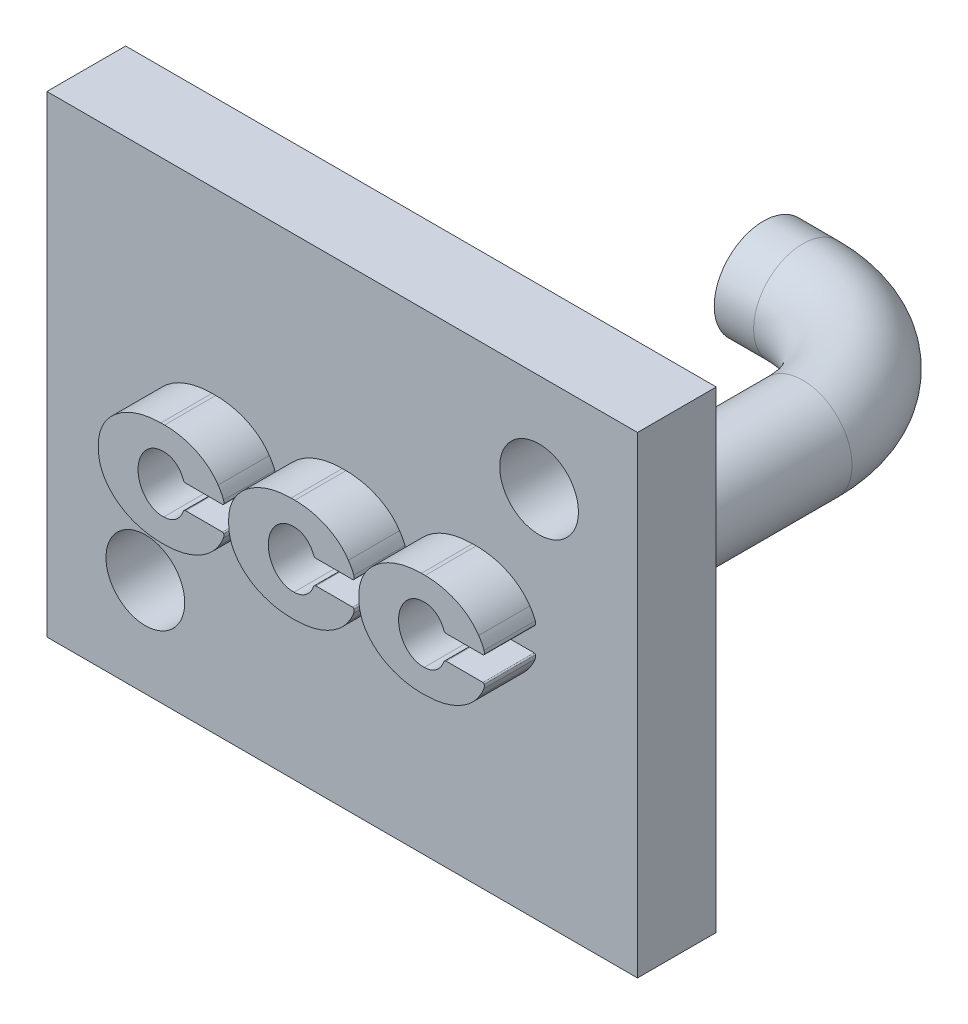
SolidWorks part; units mm, degrees
ref_plane "Front Plane" through (0, 0, 0) normal (0, 0, 1) x (1, 0, 0)
ref_plane "Top Plane" through (0, 0, 0) normal (0, 1, 0) x (1, 0, 0)
ref_plane "Right Plane" through (0, 0, 0) normal (1, 0, 0) x (0, 0, -1)
sketch "Sketch1" plane through (0, 0, 0) normal (0, 0, 1) x (1, 0, 0)
  line L1 (-7.5, 6) -> (7.5, 6)
  line L2 (-7.5, 6) -> (-7.5, -6)
  line L3 (-7.5, -6) -> (7.5, -6)
  line L4 (7.5, 6) -> (7.5, -6)
  line L5 (-7.5, 6) -> (7.5, -6) construction
  line L6 (-7.5, -6) -> (7.5, 6) construction
  point P0 (0, 0)
  dimension "D1" = 15
  dimension "D2" = 12
extrude "Boss-Extrude1" add sketch "Sketch1" along normal blind 2
sketch "Sketch2" plane through (0, 0, 2) normal (0, 0, 1) x (1, 0, 0)
  line L0 (0.6342, 0.4466) -> (1.5701, 0.4466)
  line L1 (0.0969, 1.4574) -> (0.0032, 1.4574)
  line L2 (-1.5824, 0.2062) -> (-1.5824, 0.0761)
  line L3 (0.0032, -1.1751) -> (0.0969, -1.1751)
  line L4 (1.5655, -0.1604) -> (0.6342, -0.1604)
  line L5 (-2.6741, 0.4466) -> (-1.7382, 0.4466)
  line L6 (-3.2115, 1.4574) -> (-3.3051, 1.4574)
  line L7 (-4.8907, 0.2062) -> (-4.8907, 0.0761)
  line L8 (-3.3051, -1.1751) -> (-3.2115, -1.1751)
  line L9 (-1.7428, -0.1604) -> (-2.6741, -0.1604)
  line L10 (3.9425, 0.4466) -> (4.8784, 0.4466)
  line L11 (3.4052, 1.4574) -> (3.3115, 1.4574)
  line L12 (1.7259, 0.2062) -> (1.7259, 0.0761)
  line L13 (3.3115, -1.1751) -> (3.4052, -1.1751)
  line L14 (4.8738, -0.1604) -> (3.9425, -0.1604)
  arc A0 (0.5725, 0.4902) -> (0.6342, 0.4466) centre (0.6342, 0.5121) ccw
  arc A1 (1.5701, 0.4466) -> (1.5993, 0.4715) centre (1.5656, 0.4815) ccw
  arc A2 (1.5993, 0.4715) -> (1.5951, 0.559) centre (1.4187, 0.5067) ccw
  arc A3 (1.5951, 0.559) -> (1.458, 0.8163) centre (0.5131, 0.1474) ccw
  arc A4 (1.458, -0.5339) -> (1.5904, -0.2876) centre (0.5225, 0.1277) ccw
  arc A5 (1.5904, -0.2876) -> (1.6002, -0.1896) centre (1.4189, -0.2209) ccw
  arc A6 (1.6002, -0.1896) -> (1.5655, -0.1604) centre (1.5655, -0.1956) ccw
  arc A7 (0.6342, -0.1604) -> (0.5725, -0.204) centre (0.6342, -0.2259) ccw
  arc A8 (-2.7358, 0.4902) -> (-2.6741, 0.4466) centre (-2.6741, 0.5121) ccw
  arc A9 (-1.7382, 0.4466) -> (-1.709, 0.4715) centre (-1.7427, 0.4815) ccw
  arc A10 (-1.709, 0.4715) -> (-1.7132, 0.559) centre (-1.8896, 0.5067) ccw
  arc A11 (-1.7132, 0.559) -> (-1.8504, 0.8163) centre (-2.7952, 0.1474) ccw
  arc A12 (-1.8504, -0.5339) -> (-1.7179, -0.2876) centre (-2.7858, 0.1277) ccw
  arc A13 (-1.7179, -0.2876) -> (-1.7081, -0.1896) centre (-1.8894, -0.2209) ccw
  arc A14 (-1.7081, -0.1896) -> (-1.7428, -0.1604) centre (-1.7428, -0.1956) ccw
  arc A15 (-2.6741, -0.1604) -> (-2.7358, -0.204) centre (-2.6741, -0.2259) ccw
  arc A16 (3.8808, 0.4902) -> (3.9425, 0.4466) centre (3.9425, 0.5121) ccw
  arc A17 (4.8784, 0.4466) -> (4.9076, 0.4715) centre (4.8739, 0.4815) ccw
  arc A18 (4.9076, 0.4715) -> (4.9034, 0.559) centre (4.727, 0.5067) ccw
  arc A19 (4.9034, 0.559) -> (4.7663, 0.8163) centre (3.8214, 0.1474) ccw
  arc A20 (4.7663, -0.5339) -> (4.8987, -0.2876) centre (3.8308, 0.1277) ccw
  arc A21 (4.8987, -0.2876) -> (4.9085, -0.1896) centre (4.7272, -0.2209) ccw
  arc A22 (4.9085, -0.1896) -> (4.8738, -0.1604) centre (4.8738, -0.1956) ccw
  arc A23 (3.9425, -0.1604) -> (3.8808, -0.204) centre (3.9425, -0.2259) ccw
  ellipse E0 centre (0.0443, 0.1413) end of major axis (0.0479, -0.5758) minor radius 0.6209 (0.0163, 0.8577) -> (0.0761, -0.5749) ccw
  ellipse E1 centre (-0.0118, 0.1413) end of major axis (-0.2944, -0.5403) minor radius 0.6039 (0.5725, 0.4902) -> (0.0163, 0.8577) ccw
  ellipse E2 centre (-0.0252, 0.1557) end of major axis (-1.668, -0.0894) minor radius 1.2925 (1.458, 0.8163) -> (0.0969, 1.4574) ccw
  ellipse E3 centre (0.0656, 0.157) end of major axis (-1.5793, 0.2864) minor radius 1.2979 (0.0032, 1.4574) -> (-1.5824, 0.2062) ccw
  ellipse E4 centre (0.0656, 0.1253) end of major axis (1.7105, 0.2547) minor radius 1.2979 (-1.5824, 0.0761) -> (0.0032, -1.1751) ccw
  ellipse E5 centre (-0.0252, 0.1266) end of major axis (1.6176, -0.1186) minor radius 1.2925 (0.0969, -1.1751) -> (1.458, -0.5339) ccw
  ellipse E6 centre (-0.0118, 0.1449) end of major axis (-0.2944, 0.8265) minor radius 0.6039 (0.0761, -0.5749) -> (0.5725, -0.204) ccw
  ellipse E7 centre (-3.3201, 0.1413) end of major axis (-3.6027, -0.5403) minor radius 0.6039 (-2.7358, 0.4902) -> (-3.292, 0.8577) ccw
  ellipse E8 centre (-3.3335, 0.1557) end of major axis (-1.6907, 0.4009) minor radius 1.2925 (-1.8504, 0.8163) -> (-3.2115, 1.4574) ccw
  ellipse E9 centre (-3.2427, 0.157) end of major axis (-1.5978, 0.0277) minor radius 1.2979 (-3.3051, 1.4574) -> (-4.8907, 0.2062) ccw
  ellipse E10 centre (-3.2427, 0.1253) end of major axis (-1.5978, 0.2547) minor radius 1.2979 (-4.8907, 0.0761) -> (-3.3051, -1.1751) ccw
  ellipse E11 centre (-3.3335, 0.1266) end of major axis (-1.6907, -0.1186) minor radius 1.2925 (-3.2115, -1.1751) -> (-1.8504, -0.5339) ccw
  ellipse E12 centre (-3.3201, 0.1449) end of major axis (-3.6027, 0.8265) minor radius 0.6039 (-3.2323, -0.5749) -> (-2.7358, -0.204) ccw
  ellipse E13 centre (-3.264, 0.1413) end of major axis (-3.2604, -0.5758) minor radius 0.6209 (-3.292, 0.8577) -> (-3.2323, -0.5749) ccw
  ellipse E14 centre (3.3526, 0.1413) end of major axis (3.3562, -0.5758) minor radius 0.6209 (3.3246, 0.8577) -> (3.3844, -0.5749) ccw
  ellipse E15 centre (3.2965, 0.1413) end of major axis (3.5792, 0.8229) minor radius 0.6039 (3.8808, 0.4902) -> (3.3246, 0.8577) ccw
  ellipse E16 centre (3.2831, 0.1557) end of major axis (4.9259, 0.4009) minor radius 1.2925 (4.7663, 0.8163) -> (3.4052, 1.4574) ccw
  ellipse E17 centre (3.3739, 0.157) end of major axis (1.729, 0.2864) minor radius 1.2979 (3.3115, 1.4574) -> (1.7259, 0.2062) ccw
  ellipse E18 centre (3.3739, 0.1253) end of major axis (5.0188, 0.2547) minor radius 1.2979 (1.7259, 0.0761) -> (3.3115, -1.1751) ccw
  ellipse E19 centre (3.2831, 0.1266) end of major axis (1.6403, 0.3717) minor radius 1.2925 (3.4052, -1.1751) -> (4.7663, -0.5339) ccw
  ellipse E20 centre (3.2965, 0.1449) end of major axis (3.0139, 0.8265) minor radius 0.6039 (3.3844, -0.5749) -> (3.8808, -0.204) ccw
extrude "Boss-Extrude2" add sketch "Sketch2" along normal blind 2
sketch "Sketch8" plane through (0, 0, 0) normal (0, 0, -1) x (-1, 0, 0)
  line L0 (1.1, 0) -> (-1.1, 0) construction
  line L1 (0, 0) -> (0, 0.75) construction
  line L3 (0, 6) -> (0, -6) construction
  line L4 (-7.5, 6) -> (7.5, 6) construction
  line L5 (7.5, -6) -> (-7.5, -6) construction
  circle A0 centre (1, 0) radius 1.25
  circle A1 centre (-3.7443, 0) radius 1.25 construction
  dimension "D1" = 2.5
  dimension "D2" = 2.5
  dimension "D3" = 1
extrude "Boss-Extrude4" add sketch "Sketch8" along normal blind 4.5
sketch "Sketch7" plane through (0, 0, 0) normal (0, 0, -1) x (-1, 0, 0)
  line L0 (7.8375, 0) -> (-7.8375, 0) construction
  circle A0 centre (5.3, 0) radius 1.25
  dimension "D1" = 2.5
  dimension "D2" = 5.3
extrude "Boss-Extrude5" add sketch "Sketch7" along normal blind 4.5
sketch "Sketch9" plane through (0, 0, 0) normal (0, 1, 0) x (1, 0, 0)
  line L0 (3.6987, -2) -> (3.6987, 9) construction
  line L1 (7.5, 0) -> (-7.5, 0) construction
  line L2 (3.6987, 9) -> (-0.3013, 9) construction
  line L3 (3.6987, -0.2249) -> (3.6987, 6)
  line L4 (-0.3013, 9) -> (0.6987, 9)
  arc A0 (3.6987, 6) -> (0.6987, 9) centre (0.6987, 6) ccw
  dimension "D2" = 3
  dimension "D1" = 9
  dimension "D3" = 4
  dimension "D4" = 3.6987
sketch "Sketch10" plane through (0, 0, 0) normal (0, 0, -1) x (-1, 0, 0)
  line L0 (-0.6987, 0) -> (-3.6987, 0) construction
  line L1 (-3.6987, 0) -> (0.3013, 0) construction
  circle A0 centre (-3.6987, 0) radius 1.25
  dimension "D1" = 2.5
sweep "Sweep4" add profiles "Sketch10" path "Sketch9"
sketch "Sketch11" plane through (0, 0, 2) normal (0, 0, 1) x (1, 0, 0)
  line L0 (7.5, 6) -> (-7.5, 6) construction
  line L1 (7.5, -6) -> (7.5, 6) construction
  line L2 (-7.5, -6) -> (7.5, -6) construction
  line L3 (-7.5, 6) -> (-7.5, -6) construction
  circle A0 centre (-5, -3.5) radius 1
  circle A1 centre (5, 3.5) radius 1
  dimension "D5" = 2
  dimension "D1" = 2.5
  dimension "D2" = 2.5
  dimension "D3" = 2.5
  dimension "D4" = 2.5
extrude "Cut-Extrude1" cut sketch "Sketch11" against normal through all
sketch "Sketch13" plane through (0, 0, 4) normal (0, 0, 1) x (1, 0, 0)
  line L0 (0.6342, 0.4466) -> (1.5701, 0.4466) construction
  line L1 (0.0969, 1.4574) -> (0.0032, 1.4574) construction
  line L2 (-1.5824, 0.2062) -> (-1.5824, 0.0761) construction
  line L3 (0.0032, -1.1751) -> (0.0969, -1.1751) construction
  line L4 (1.5655, -0.1604) -> (0.6342, -0.1604) construction
  line L5 (-2.6741, 0.4466) -> (-1.7382, 0.4466)
  line L6 (-3.2115, 1.4574) -> (-3.3051, 1.4574)
  line L7 (-4.8907, 0.2062) -> (-4.8907, 0.0761)
  line L8 (-3.3051, -1.1751) -> (-3.2115, -1.1751)
  line L9 (-1.7428, -0.1604) -> (-2.6741, -0.1604)
  line L10 (-2.6741, 0.4466) -> (-1.7382, 0.4466)
  line L11 (-3.2115, 1.4574) -> (-3.3051, 1.4574)
  line L12 (-4.8907, 0.2062) -> (-4.8907, 0.0761)
  line L13 (-3.3051, -1.1751) -> (-3.2115, -1.1751)
  line L14 (-1.7428, -0.1604) -> (-2.6741, -0.1604)
  line L15 (3.9425, 0.4466) -> (4.8784, 0.4466) construction
  line L16 (3.4052, 1.4574) -> (3.3115, 1.4574) construction
  line L17 (1.7259, 0.2062) -> (1.7259, 0.0761) construction
  line L18 (3.3115, -1.1751) -> (3.4052, -1.1751) construction
  line L19 (4.8738, -0.1604) -> (3.9425, -0.1604) construction
  line L20 (0.6342, 0.4466) -> (1.5701, 0.4466)
  line L21 (0.0969, 1.4574) -> (0.0032, 1.4574)
  line L22 (-1.5824, 0.2062) -> (-1.5824, 0.0761)
  line L23 (0.0032, -1.1751) -> (0.0969, -1.1751)
  line L24 (1.5655, -0.1604) -> (0.6342, -0.1604)
  line L25 (3.9425, 0.4466) -> (4.8784, 0.4466)
  line L26 (3.4052, 1.4574) -> (3.3115, 1.4574)
  line L27 (1.7259, 0.2062) -> (1.7259, 0.0761)
  line L28 (3.3115, -1.1751) -> (3.4052, -1.1751)
  line L29 (4.8738, -0.1604) -> (3.9425, -0.1604)
  arc A0 (0.5725, 0.4902) -> (0.6342, 0.4466) centre (0.6342, 0.5121) ccw construction
  arc A1 (1.5701, 0.4466) -> (1.5993, 0.4715) centre (1.5656, 0.4815) ccw construction
  arc A2 (1.5993, 0.4715) -> (1.5951, 0.559) centre (1.4187, 0.5067) ccw construction
  arc A3 (1.5951, 0.559) -> (1.458, 0.8163) centre (0.5131, 0.1474) ccw construction
  arc A4 (1.458, -0.5339) -> (1.5904, -0.2876) centre (0.5225, 0.1277) ccw construction
  arc A5 (1.5904, -0.2876) -> (1.6002, -0.1896) centre (1.4189, -0.2209) ccw construction
  arc A6 (1.6002, -0.1896) -> (1.5655, -0.1604) centre (1.5655, -0.1956) ccw construction
  arc A7 (0.6342, -0.1604) -> (0.5725, -0.204) centre (0.6342, -0.2259) ccw construction
  arc A8 (-2.7358, 0.4902) -> (-2.6741, 0.4466) centre (-2.6741, 0.5121) ccw
  arc A9 (-1.7382, 0.4466) -> (-1.709, 0.4715) centre (-1.7427, 0.4815) ccw
  arc A10 (-1.709, 0.4715) -> (-1.7132, 0.559) centre (-1.8896, 0.5067) ccw
  arc A11 (-1.7132, 0.559) -> (-1.8504, 0.8163) centre (-2.7952, 0.1474) ccw
  arc A12 (-1.8504, -0.5339) -> (-1.7179, -0.2876) centre (-2.7858, 0.1277) ccw
  arc A13 (-1.7179, -0.2876) -> (-1.7081, -0.1896) centre (-1.8894, -0.2209) ccw
  arc A14 (-1.7081, -0.1896) -> (-1.7428, -0.1604) centre (-1.7428, -0.1956) ccw
  arc A15 (-2.6741, -0.1604) -> (-2.7358, -0.204) centre (-2.6741, -0.2259) ccw
  arc A16 (-2.7358, 0.4902) -> (-2.6741, 0.4466) centre (-2.6741, 0.5121) ccw
  arc A17 (-1.7382, 0.4466) -> (-1.709, 0.4715) centre (-1.7427, 0.4815) ccw
  arc A18 (-1.709, 0.4715) -> (-1.7132, 0.559) centre (-1.8896, 0.5067) ccw
  arc A19 (-1.7132, 0.559) -> (-1.8504, 0.8163) centre (-2.7952, 0.1474) ccw
  arc A20 (-1.8504, -0.5339) -> (-1.7179, -0.2876) centre (-2.7858, 0.1277) ccw
  arc A21 (-1.7179, -0.2876) -> (-1.7081, -0.1896) centre (-1.8894, -0.2209) ccw
  arc A22 (-1.7081, -0.1896) -> (-1.7428, -0.1604) centre (-1.7428, -0.1956) ccw
  arc A23 (-2.6741, -0.1604) -> (-2.7358, -0.204) centre (-2.6741, -0.2259) ccw
  arc A24 (3.8808, 0.4902) -> (3.9425, 0.4466) centre (3.9425, 0.5121) ccw construction
  arc A25 (4.8784, 0.4466) -> (4.9076, 0.4715) centre (4.8739, 0.4815) ccw construction
  arc A26 (4.9076, 0.4715) -> (4.9034, 0.559) centre (4.727, 0.5067) ccw construction
  arc A27 (4.9034, 0.559) -> (4.7663, 0.8163) centre (3.8214, 0.1474) ccw construction
  arc A28 (4.7663, -0.5339) -> (4.8987, -0.2876) centre (3.8308, 0.1277) ccw construction
  arc A29 (4.8987, -0.2876) -> (4.9085, -0.1896) centre (4.7272, -0.2209) ccw construction
  arc A30 (4.9085, -0.1896) -> (4.8738, -0.1604) centre (4.8738, -0.1956) ccw construction
  arc A31 (3.9425, -0.1604) -> (3.8808, -0.204) centre (3.9425, -0.2259) ccw construction
  arc A32 (0.5725, 0.4902) -> (0.6342, 0.4466) centre (0.6342, 0.5121) ccw
  arc A33 (1.5701, 0.4466) -> (1.5993, 0.4715) centre (1.5656, 0.4815) ccw
  arc A34 (1.5993, 0.4715) -> (1.5951, 0.559) centre (1.4187, 0.5067) ccw
  arc A35 (1.5951, 0.559) -> (1.458, 0.8163) centre (0.5131, 0.1474) ccw
  arc A36 (1.458, -0.5339) -> (1.5904, -0.2876) centre (0.5225, 0.1277) ccw
  arc A37 (1.5904, -0.2876) -> (1.6002, -0.1896) centre (1.4189, -0.2209) ccw
  arc A38 (1.6002, -0.1896) -> (1.5655, -0.1604) centre (1.5655, -0.1956) ccw
  arc A39 (0.6342, -0.1604) -> (0.5725, -0.204) centre (0.6342, -0.2259) ccw
  arc A40 (3.8808, 0.4902) -> (3.9425, 0.4466) centre (3.9425, 0.5121) ccw
  arc A41 (4.8784, 0.4466) -> (4.9076, 0.4715) centre (4.8739, 0.4815) ccw
  arc A42 (4.9076, 0.4715) -> (4.9034, 0.559) centre (4.727, 0.5067) ccw
  arc A43 (4.9034, 0.559) -> (4.7663, 0.8163) centre (3.8214, 0.1474) ccw
  arc A44 (4.7663, -0.5339) -> (4.8987, -0.2876) centre (3.8308, 0.1277) ccw
  arc A45 (4.8987, -0.2876) -> (4.9085, -0.1896) centre (4.7272, -0.2209) ccw
  arc A46 (4.9085, -0.1896) -> (4.8738, -0.1604) centre (4.8738, -0.1956) ccw
  arc A47 (3.9425, -0.1604) -> (3.8808, -0.204) centre (3.9425, -0.2259) ccw
  ellipse E0 centre (-0.0118, 0.1413) end of major axis (-0.2944, -0.5403) minor radius 0.6039 (0.5725, 0.4902) -> (0.0163, 0.8577) ccw construction
  ellipse E1 centre (-0.0252, 0.1557) end of major axis (1.6176, 0.4009) minor radius 1.2925 (1.458, 0.8163) -> (0.0969, 1.4574) ccw construction
  ellipse E2 centre (0.0656, 0.157) end of major axis (-1.5793, 0.2864) minor radius 1.2979 (0.0032, 1.4574) -> (-1.5824, 0.2062) ccw construction
  ellipse E3 centre (0.0656, 0.1253) end of major axis (1.7105, 0.2547) minor radius 1.2979 (-1.5824, 0.0761) -> (0.0032, -1.1751) ccw construction
  ellipse E4 centre (-0.0252, 0.1266) end of major axis (-1.668, 0.3717) minor radius 1.2925 (0.0969, -1.1751) -> (1.458, -0.5339) ccw construction
  ellipse E5 centre (-0.0118, 0.1449) end of major axis (0.2709, -0.5367) minor radius 0.6039 (0.0761, -0.5749) -> (0.5725, -0.204) ccw construction
  ellipse E6 centre (0.0443, 0.1413) end of major axis (0.0479, -0.5758) minor radius 0.6209 (0.0163, 0.8577) -> (0.0761, -0.5749) ccw construction
  ellipse E7 centre (-3.3201, 0.1413) end of major axis (-3.6027, -0.5403) minor radius 0.6039 (-2.7358, 0.4902) -> (-3.292, 0.8577) ccw
  ellipse E8 centre (-3.3335, 0.1557) end of major axis (-4.9763, -0.0894) minor radius 1.2925 (-1.8504, 0.8163) -> (-3.2115, 1.4574) ccw
  ellipse E9 centre (-3.2427, 0.157) end of major axis (-4.8876, 0.2864) minor radius 1.2979 (-3.3051, 1.4574) -> (-4.8907, 0.2062) ccw
  ellipse E10 centre (-3.2427, 0.1253) end of major axis (-1.5978, 0.2547) minor radius 1.2979 (-4.8907, 0.0761) -> (-3.3051, -1.1751) ccw
  ellipse E11 centre (-3.3335, 0.1266) end of major axis (-1.6907, -0.1186) minor radius 1.2925 (-3.2115, -1.1751) -> (-1.8504, -0.5339) ccw
  ellipse E12 centre (-3.3201, 0.1449) end of major axis (-3.0375, -0.5367) minor radius 0.6039 (-3.2323, -0.5749) -> (-2.7358, -0.204) ccw
  ellipse E13 centre (-3.264, 0.1413) end of major axis (-3.2604, -0.5758) minor radius 0.6209 (-3.292, 0.8577) -> (-3.2323, -0.5749) ccw
  ellipse E14 centre (-3.3201, 0.1413) end of major axis (-3.6027, -0.5403) minor radius 0.6039 (-2.7358, 0.4902) -> (-3.292, 0.8577) ccw
  ellipse E15 centre (-3.3335, 0.1557) end of major axis (-4.9763, -0.0894) minor radius 1.2925 (-1.8504, 0.8163) -> (-3.2115, 1.4574) ccw
  ellipse E16 centre (-3.2427, 0.157) end of major axis (-4.8876, 0.2864) minor radius 1.2979 (-3.3051, 1.4574) -> (-4.8907, 0.2062) ccw
  ellipse E17 centre (-3.2427, 0.1253) end of major axis (-1.5978, 0.2547) minor radius 1.2979 (-4.8907, 0.0761) -> (-3.3051, -1.1751) ccw
  ellipse E18 centre (-3.3335, 0.1266) end of major axis (-4.9763, 0.3717) minor radius 1.2925 (-3.2115, -1.1751) -> (-1.8504, -0.5339) ccw
  ellipse E19 centre (-3.3201, 0.1449) end of major axis (-3.0375, -0.5367) minor radius 0.6039 (-3.2323, -0.5749) -> (-2.7358, -0.204) ccw
  ellipse E20 centre (-3.264, 0.1413) end of major axis (-3.2604, -0.5758) minor radius 0.6209 (-3.292, 0.8577) -> (-3.2323, -0.5749) ccw
  ellipse E21 centre (3.2965, 0.1413) end of major axis (3.0139, -0.5403) minor radius 0.6039 (3.8808, 0.4902) -> (3.3246, 0.8577) ccw construction
  ellipse E22 centre (3.2831, 0.1557) end of major axis (1.6403, -0.0894) minor radius 1.2925 (4.7663, 0.8163) -> (3.4052, 1.4574) ccw construction
  ellipse E23 centre (3.3739, 0.157) end of major axis (1.729, 0.2864) minor radius 1.2979 (3.3115, 1.4574) -> (1.7259, 0.2062) ccw construction
  ellipse E24 centre (3.3739, 0.1253) end of major axis (1.729, -0.004) minor radius 1.2979 (1.7259, 0.0761) -> (3.3115, -1.1751) ccw construction
  ellipse E25 centre (3.2831, 0.1266) end of major axis (1.6403, 0.3717) minor radius 1.2925 (3.4052, -1.1751) -> (4.7663, -0.5339) ccw construction
  ellipse E26 centre (3.2965, 0.1449) end of major axis (3.5792, -0.5367) minor radius 0.6039 (3.3844, -0.5749) -> (3.8808, -0.204) ccw construction
  ellipse E27 centre (3.3526, 0.1413) end of major axis (3.3562, -0.5758) minor radius 0.6209 (3.3246, 0.8577) -> (3.3844, -0.5749) ccw construction
  ellipse E28 centre (-0.0118, 0.1413) end of major axis (-0.2944, -0.5403) minor radius 0.6039 (0.5725, 0.4902) -> (0.0163, 0.8577) ccw
  ellipse E29 centre (-0.0252, 0.1557) end of major axis (1.6176, 0.4009) minor radius 1.2925 (1.458, 0.8163) -> (0.0969, 1.4574) ccw
  ellipse E30 centre (0.0656, 0.157) end of major axis (-1.5793, 0.2864) minor radius 1.2979 (0.0032, 1.4574) -> (-1.5824, 0.2062) ccw
  ellipse E31 centre (0.0656, 0.1253) end of major axis (1.7105, 0.2547) minor radius 1.2979 (-1.5824, 0.0761) -> (0.0032, -1.1751) ccw
  ellipse E32 centre (-0.0252, 0.1266) end of major axis (-1.668, 0.3717) minor radius 1.2925 (0.0969, -1.1751) -> (1.458, -0.5339) ccw
  ellipse E33 centre (-0.0118, 0.1449) end of major axis (0.2709, -0.5367) minor radius 0.6039 (0.0761, -0.5749) -> (0.5725, -0.204) ccw
  ellipse E34 centre (0.0443, 0.1413) end of major axis (0.0479, -0.5758) minor radius 0.6209 (0.0163, 0.8577) -> (0.0761, -0.5749) ccw
  ellipse E35 centre (3.2965, 0.1413) end of major axis (3.0139, -0.5403) minor radius 0.6039 (3.8808, 0.4902) -> (3.3246, 0.8577) ccw
  ellipse E36 centre (3.2831, 0.1557) end of major axis (4.9259, 0.4009) minor radius 1.2925 (4.7663, 0.8163) -> (3.4052, 1.4574) ccw
  ellipse E37 centre (3.3739, 0.157) end of major axis (1.729, 0.2864) minor radius 1.2979 (3.3115, 1.4574) -> (1.7259, 0.2062) ccw
  ellipse E38 centre (3.3739, 0.1253) end of major axis (5.0188, 0.2547) minor radius 1.2979 (1.7259, 0.0761) -> (3.3115, -1.1751) ccw
  ellipse E39 centre (3.2831, 0.1266) end of major axis (1.6403, 0.3717) minor radius 1.2925 (3.4052, -1.1751) -> (4.7663, -0.5339) ccw
  ellipse E40 centre (3.2965, 0.1449) end of major axis (3.5792, -0.5367) minor radius 0.6039 (3.3844, -0.5749) -> (3.8808, -0.204) ccw
  ellipse E41 centre (3.3526, 0.1413) end of major axis (3.3562, -0.5758) minor radius 0.6209 (3.3246, 0.8577) -> (3.3844, -0.5749) ccw
  dimension "D1" = 0
extrude "Cut-Extrude2" cut sketch "Sketch13" against normal blind 0.7
